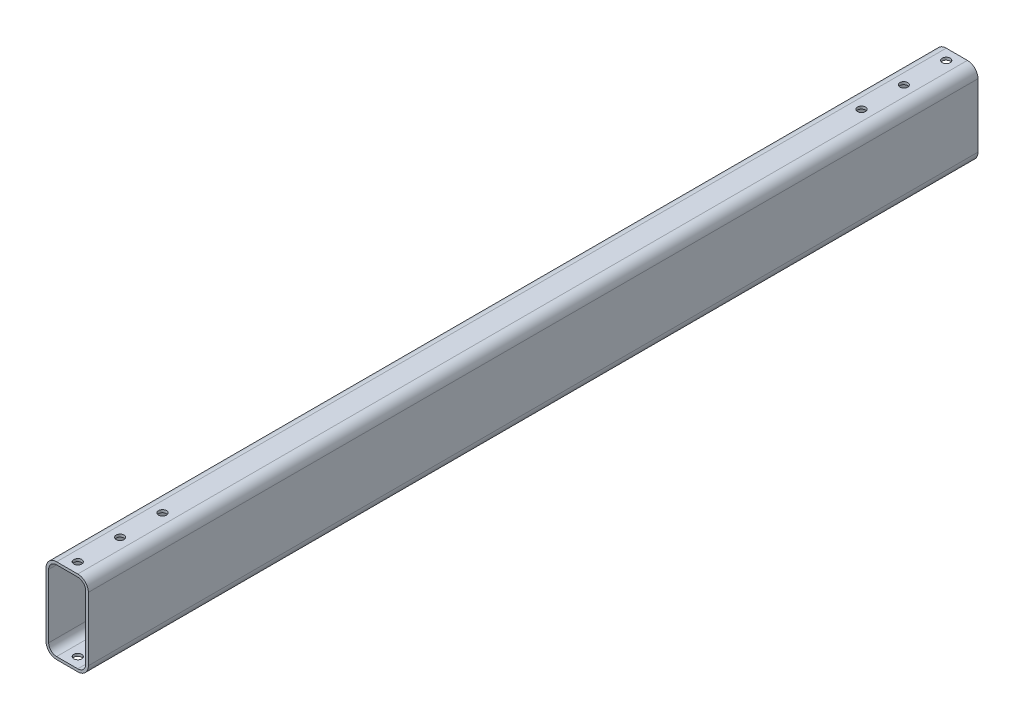
SolidWorks part; units mm, degrees
material "6061-T6 (SS)"
ref_plane "Front Plane" through (0, 0, 0) normal (0, 0, 1) x (1, 0, 0)
ref_plane "Top Plane" through (0, 0, 0) normal (0, 1, 0) x (1, 0, 0)
ref_plane "Right Plane" through (0, 0, 0) normal (1, 0, 0) x (0, 0, -1)
sketch "Sketch1" plane through (0, 0, 0) normal (0, 0, 1) x (1, 0, 0)
  line L1 (-6.35, -25.4) -> (6.35, -25.4)
  line L2 (-12.7, -19.05) -> (-12.7, 19.05)
  line L3 (-6.35, 25.4) -> (6.35, 25.4)
  line L4 (12.7, -19.05) -> (12.7, 19.05)
  line L5 (-12.7, -25.4) -> (12.7, 25.4) construction
  line L6 (-12.7, 25.4) -> (12.7, -25.4) construction
  arc A0 (-12.7, -19.05) -> (-6.35, -25.4) centre (-6.35, -19.05) ccw
  arc A1 (6.35, -25.4) -> (12.7, -19.05) centre (6.35, -19.05) ccw
  arc A2 (6.35, 25.4) -> (12.7, 19.05) centre (6.35, 19.05) cw
  arc A3 (-12.7, 19.05) -> (-6.35, 25.4) centre (-6.35, 19.05) cw
  point P0 (0, 0)
  dimension "D3" = 6.35
  dimension "D1" = 50.8
  dimension "D2" = 25.4
extrude "Extrude-Thin1" add sketch "Sketch1" along normal blind 533.4 thin thin type one direction reverse wall 1.5875
hole_wizard "3/16 (0.1875) Diameter Hole1" positions "3DSketch1" profile "Sketch3" hole size "3/16" standard "ANSI Inch" end condition through all
sketch3d "3DSketch1"
  line L1 (6.35, 25.4, 0) -> (-6.35, 25.4, 0) construction
  line L6 (0, 25.4, 533.4) -> (0, 25.4, 0) construction
  line L7 (6.35, 25.4, 533.4) -> (-6.35, 25.4, 533.4) construction
  point P57 (0, 25.4, 6.35)
  point P59 (0, 25.4, 31.75)
  point P61 (0, 25.4, 57.15)
  point P63 (0, 25.4, 501.65)
  point P65 (0, 25.4, 476.25)
  point P67 (0, 25.4, 527.05)
  dimension "D1" = 25.4
  dimension "D2" = 25.4
  dimension "D3" = 6.35
  dimension "D4" = 25.4
  dimension "D5" = 25.4
  dimension "D6" = 6.35
sketch "Sketch3" plane through (0, 25.4, 527.05) normal (1, 0, 0) x (0, 0, 1)
  line L0 (0, 0) -> (0, 50.8)
  line L1 (0, 50.8) -> (2.3812, 50.8)
  line L2 (2.3812, 50.8) -> (2.3812, 0)
  line L5 (2.3812, 0) -> (0, 0)
  line L11 (0, -6.35) -> (0, 107.95) construction
  dimension "Thru Hole Dia." = 4.7625
  dimension "Thru Hole Depth" = 50.8
hole_wizard "3/16 (0.195) Diameter Hole1" positions "Sketch4" profile "Sketch5" hole size "3/16" standard "ANSI Inch"
sketch "Sketch4" plane through (0, -25.4, 0) normal (0, -1, 0) x (-1, 0, 0)
  point P0 (-6.331, -114.3163)
  point P3 (0.2817, -139.6492)
  point P6 (-5.805, -165.1136)
  point P9 (0.8077, -190.4465)
  point P15 (-3.175, -419.1)
  point P18 (2.9117, -393.6356)
  point P21 (-3.701, -368.3027)
  point P24 (2.3857, -342.8383)
  point P29 (0, 0)
sketch "Sketch5" plane through (6.331, -25.4, 114.3163) normal (1, 0, 0) x (0, 0, -1)
  line L0 (0, 0) -> (0, 1.5875)
  line L1 (0, 1.5875) -> (2.4765, 1.5875)
  line L2 (2.4765, 1.5875) -> (2.4765, 0)
  line L5 (2.4765, 0) -> (0, 0)
  line L11 (0, -6.35) -> (0, 107.95) construction
  dimension "Thru Hole Dia." = 4.953
  dimension "Thru Hole Depth" = 1.5875
